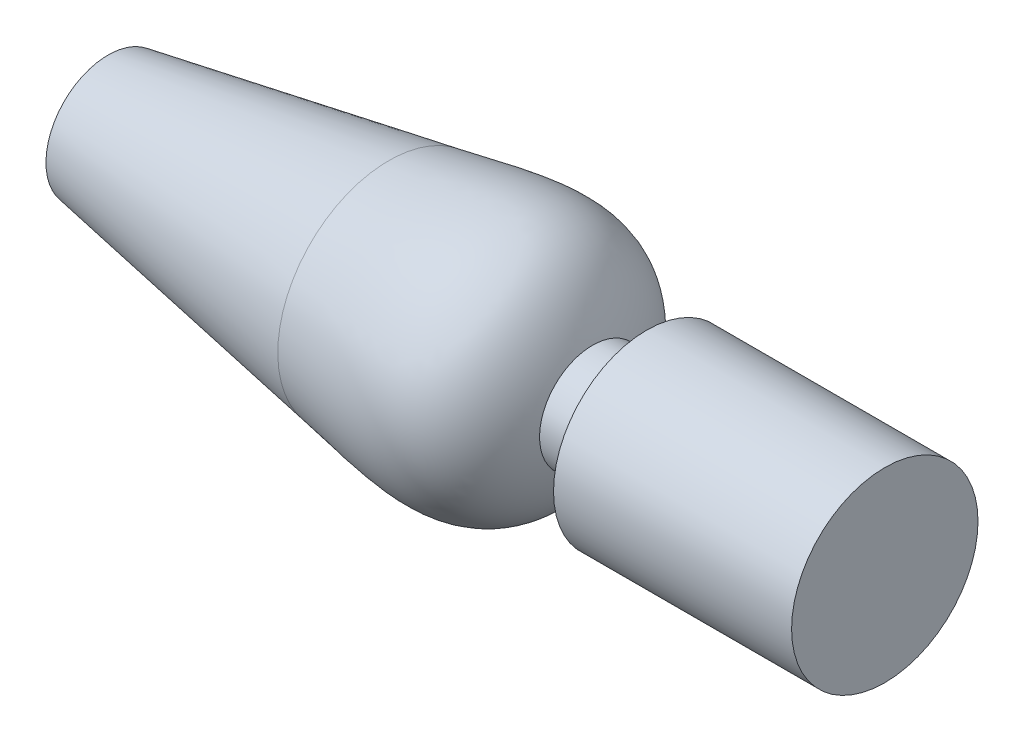
SolidWorks part; units mm, degrees
ref_plane "Front Plane" through (0, 0, 0) normal (0, 0, 1) x (1, 0, 0)
ref_plane "Top Plane" through (0, 0, 0) normal (0, 1, 0) x (1, 0, 0)
ref_plane "Right Plane" through (0, 0, 0) normal (1, 0, 0) x (0, 0, -1)
sketch "Sketch1" plane through (0, 0, 0) normal (0, 0, 1) x (1, 0, 0)
  line L0 (-6.25, 0) -> (6.25, 0) construction
  line L1 (6.25, 0) -> (6.25, 1.5)
  line L2 (6.25, 1.5) -> (2.4184, 1.5)
  line L3 (2.4184, 1.5) -> (2.4184, 0.8534)
  line L4 (2.4184, 0.8534) -> (1.5474, 0.8534)
  line L7 (-6.25, 1) -> (-6.25, 0)
  line L8 (-6.25, 0) -> (6.25, 0)
  line L9 (-1.7322, 1.7871) -> (-6.25, 1)
  spline S0 degree 3 poles (-1.7322, 1.7871) (-0.1449, 2.0637) (0.9657, 2.4392) (1.5474, 0.8534) knots 0 0 0 0 1 1 1 1
  point P0 (1.5474, 0.8534)
  point P4 (0, 0)
  point P7 (2.4184, 0.8534)
  point P10 (-6.25, 1)
  point P12 (2.4184, 1.5)
  dimension "D1" = 12.5
  dimension "D2" = 1.5
  dimension "D4" = 1
revolve "Revolve1" add sketch "Sketch1" angle 360 about L0
sketch "Sketch3" plane through (6.25, 0, 0) normal (1, 0, 0) x (0, 0, -1)
  point P0 (0, 0)
sketch3d "3DSketch1"
  line L0 (6.25, 0, 0) -> (13.7198, 0, 0) construction
